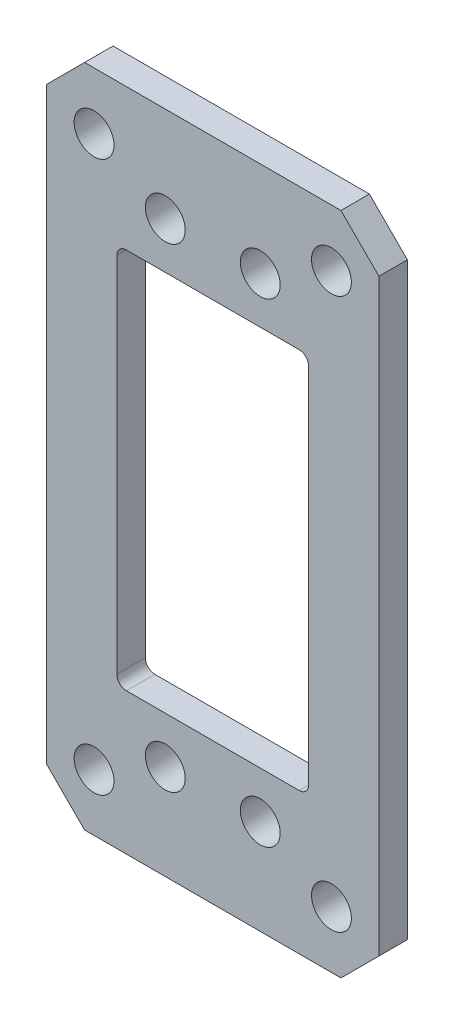
SolidWorks part; units mm, degrees
ref_plane "前基準面" through (0, 0, 0) normal (0, 0, 1) x (1, 0, 0)
ref_plane "上基準面" through (0, 0, 0) normal (0, 1, 0) x (1, 0, 0)
ref_plane "右基準面" through (0, 0, 0) normal (1, 0, 0) x (0, 0, -1)
sketch "草圖1" plane through (0, 0, 0) normal (0, 0, 1) x (1, 0, 0)
  line L1 (-17.5, -35) -> (17.5, -35)
  line L2 (-17.5, -35) -> (-17.5, 35)
  line L3 (-17.5, 35) -> (17.5, 35)
  line L4 (17.5, -35) -> (17.5, 35)
  line L5 (-17.5, -35) -> (17.5, 35) construction
  line L6 (-17.5, 35) -> (17.5, -35) construction
  point P0 (0, 0)
  dimension "D1" = 35
  dimension "D2" = 70
extrude "填料-伸長1" add sketch "草圖1" along normal blind 3
chamfer "導角1" distance 4 angle 45 4 edges at (-17.5, -35, 1.5) (17.5, -35, 1.5) (17.5, 35, 1.5) (-17.5, 35, 1.5)
sketch "草圖2" plane through (0, 0, 0) normal (0, 0, -1) x (-1, 0, 0)
  line L7 (-10.1, -20.1) -> (10.1, -20.1)
  line L8 (-10.1, -20.1) -> (-10.1, 20.1)
  line L9 (-10.1, 20.1) -> (10.1, 20.1)
  line L10 (10.1, -20.1) -> (10.1, 20.1)
  line L11 (-10.1, -20.1) -> (10.1, 20.1) construction
  line L12 (-10.1, 20.1) -> (10.1, -20.1) construction
  point P0 (0, 0)
  dimension "D1" = 40.2
  dimension "D2" = 20.2
extrude "除料-伸長1" cut sketch "草圖2" against normal through all
sketch "草圖4" plane through (0, 0, 0) normal (0, 0, -1) x (-1, 0, 0)
  line L1 (12.5, -29) -> (-12.5, -29) construction
  line L2 (12.5, -29) -> (12.5, 29) construction
  line L3 (12.5, 29) -> (-12.5, 29) construction
  line L4 (-12.5, -29) -> (-12.5, 29) construction
  line L5 (12.5, -29) -> (-12.5, 29) construction
  line L6 (12.5, 29) -> (-12.5, -29) construction
  circle A0 centre (-12.5, 29) radius 2.1
  point P0 (0, 0)
  dimension "D3" = 4.2
  dimension "D1" = 25
  dimension "D2" = 58
extrude "除料-伸長3" cut sketch "草圖4" against normal through all
pattern_linear "直線複製排列2" count 2 spacing 25 along (-1, 0, 0) count 2 spacing 58 along (0, -1, 0) of "除料-伸長3"
sketch "草圖5" plane through (0, 0, 3) normal (0, 0, 1) x (1, 0, 0)
  line L1 (-5, -25) -> (5, -25) construction
  line L2 (-5, -25) -> (-5, 25) construction
  line L3 (-5, 25) -> (5, 25) construction
  line L4 (5, -25) -> (5, 25) construction
  line L5 (-5, -25) -> (5, 25) construction
  line L6 (-5, 25) -> (5, -25) construction
  circle A2 centre (-5, -25) radius 2.1
  point P0 (0, 0)
  dimension "D3" = 4.2
  dimension "D1" = 50
  dimension "D2" = 10
extrude "除料-伸長4" cut sketch "草圖5" against normal through all and the other way through all
pattern_linear "直線複製排列3" count 2 spacing 10 along (1, 0, 0) count 2 spacing 50 along (0, 1, 0) of "除料-伸長4"
fillet "圓角1" radius 1 4 edges at (10.1, -20.1, 1.5) (-10.1, -20.1, 1.5) (10.1, 20.1, 1.5) (-10.1, 20.1, 1.5)
